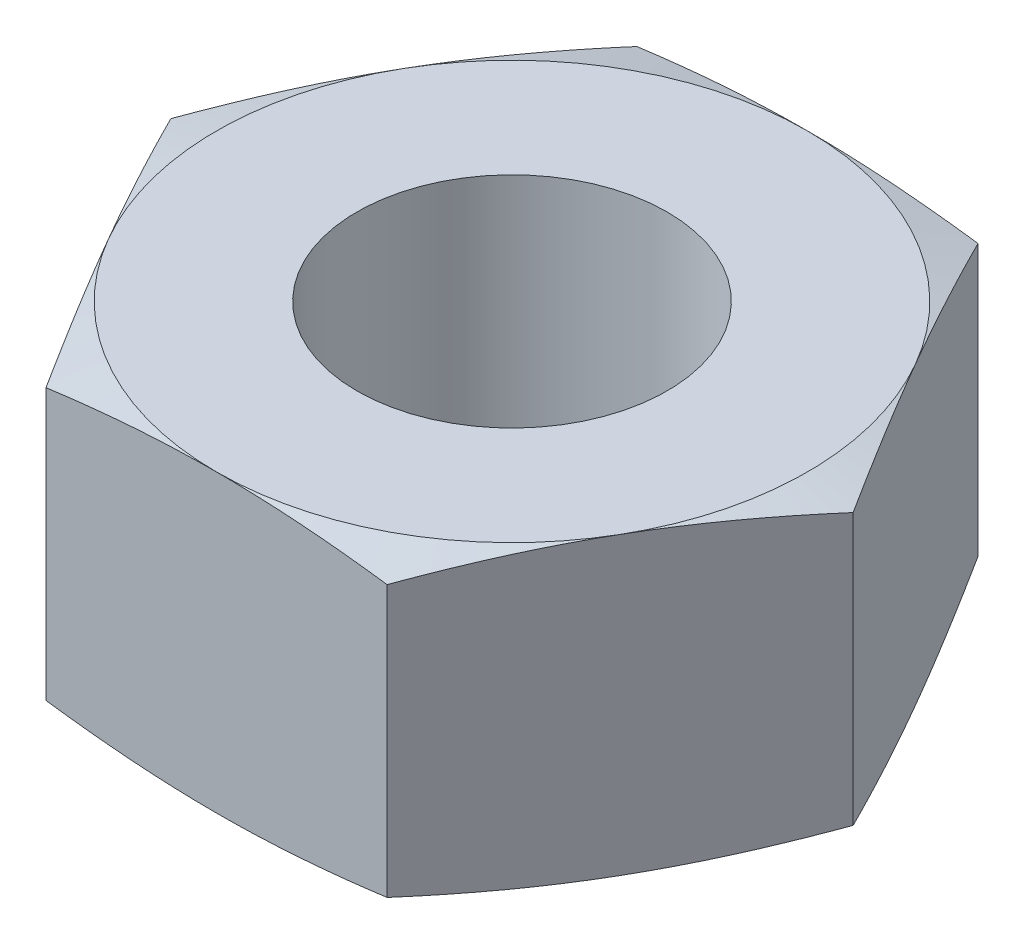
SolidWorks part; units mm, degrees
ref_plane "前视基准面" through (0, 0, 0) normal (0, 0, 1) x (1, 0, 0)
ref_plane "上视基准面" through (0, 0, 0) normal (0, 1, 0) x (1, 0, 0)
ref_plane "右视基准面" through (0, 0, 0) normal (1, 0, 0) x (0, 0, -1)
other "Configuration Table"
sketch "草图1" plane through (0, 0, 0) normal (0, 1, 0) x (1, 0, 0)
  line L1 (4.6188, 0) -> (2.3094, 4)
  line L2 (2.3094, 4) -> (-2.3094, 4)
  line L3 (-2.3094, 4) -> (-4.6188, 0)
  line L4 (-4.6188, 0) -> (-2.3094, -4)
  line L5 (-2.3094, -4) -> (2.3094, -4)
  line L6 (2.3094, -4) -> (4.6188, 0)
  circle A0 centre (0, 0) radius 4 construction
  dimension "D1" = 8
extrude "凸台-拉伸1" add sketch "草图1" along normal blind 4
hole_wizard "M5 螺纹孔1" positions "草图2" profile "草图3" tap size "M5" standard "GB" end condition through all
sketch "草图2" plane through (0, 4, 0) normal (0, 1, 0) x (1, 0, 0)
  point P0 (0, 0)
sketch "草图3" plane through (0, 4, 0) normal (1, 0, 0) x (0, 0, 1)
  line L0 (0, 0) -> (0, 4)
  line L1 (0, 4) -> (2.1, 4)
  line L2 (2.1, 4) -> (2.1, 0)
  line L5 (2.1, 0) -> (0, 0)
  line L11 (0, -6.35) -> (0, 107.95) construction
  dimension "通孔螺纹孔钻头直径" = 4.2
  dimension "通孔螺纹孔钻头深度" = 4
cosmetic thread "孔螺纹线1" parameters "D2"=5
sketch "草图4" plane through (0, 0, 0) normal (1, 0, 0) x (0, 0, -1)
  line L0 (0, 0) -> (0, -50000) construction
  line L1 (4, 2) -> (-49996, 2) construction
  line L2 (4, 4) -> (4, 0) construction
  line L3 (4, 4) -> (5.5783, 3.5771)
  line L4 (5.5783, 3.5771) -> (4.8477, 6.6442)
  line L5 (4.8477, 6.6442) -> (4, 4)
  line L6 (4.8477, -2.6442) -> (4, 0)
  line L7 (5.5783, 0.4229) -> (4.8477, -2.6442)
  line L8 (4, 0) -> (5.5783, 0.4229)
  point P7 (4, 2)
  dimension "D1" = 75
revolve "切除-旋转1" cut sketch "草图4" angle 360 about L0
